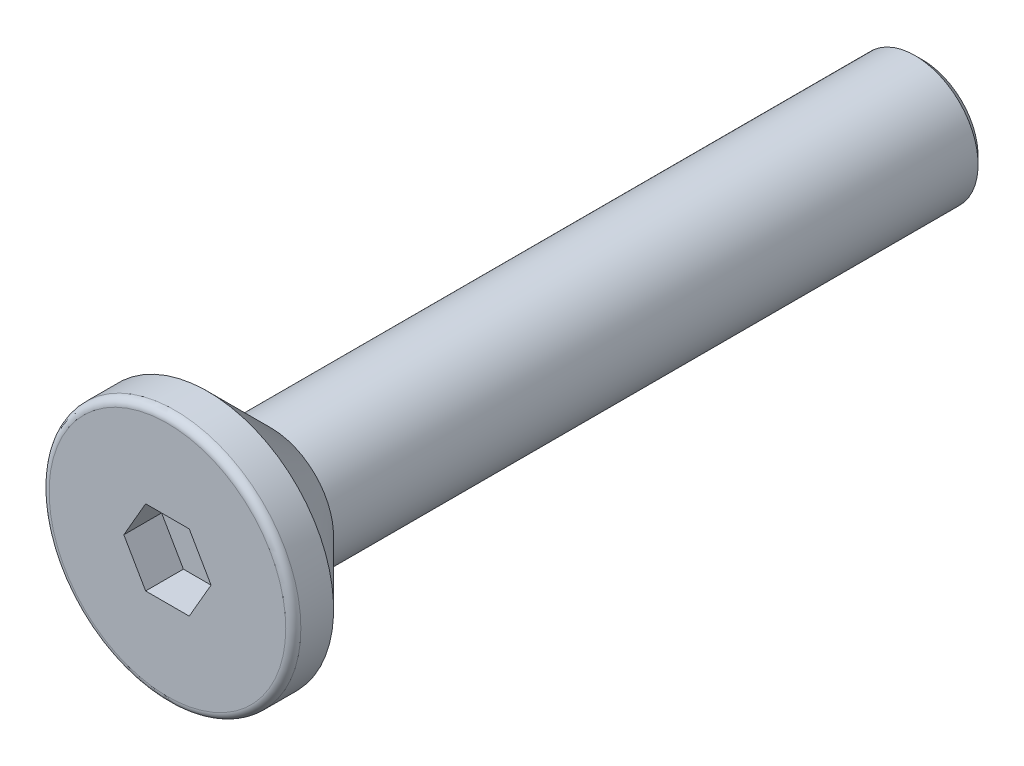
SolidWorks part; units mm, degrees
ref_plane "前视基准面" through (0, 0, 0) normal (0, 0, 1) x (1, 0, 0)
ref_plane "上视基准面" through (0, 0, 0) normal (0, 1, 0) x (1, 0, 0)
ref_plane "右视基准面" through (0, 0, 0) normal (1, 0, 0) x (0, 0, -1)
sketch "草图1" plane through (0, 0, 0) normal (1, 0, 0) x (0, 0, -1)
  line L0 (-15, 0) -> (-15, 5)
  line L1 (-15, 5) -> (-13.4, 5)
  line L2 (-13.4, 5) -> (-10.9, 2.5)
  line L3 (-10.9, 2.5) -> (14.7, 2.5)
  line L4 (14.7, 2.5) -> (15, 2.2)
  line L5 (15, 2.2) -> (15, 0)
  line L6 (15, 0) -> (-15, 0)
  dimension "D1" = 30
  dimension "D2" = 5
  dimension "D3" = 45
  dimension "D4" = 0.3
  dimension "D5" = 4.1
  dimension "D6" = 2.5
revolve "旋转1" add sketch "草图1" angle 360 about L6
sketch "草图2" plane through (0, 0, 15) normal (0, 0, 1) x (1, 0, 0)
  line L1 (1.7321, 0) -> (0.866, 1.5)
  line L2 (0.866, 1.5) -> (-0.866, 1.5)
  line L3 (-0.866, 1.5) -> (-1.7321, 0)
  line L4 (-1.7321, 0) -> (-0.866, -1.5)
  line L5 (-0.866, -1.5) -> (0.866, -1.5)
  line L6 (0.866, -1.5) -> (1.7321, 0)
  circle A0 centre (0, 0) radius 1.5 construction
  dimension "D1" = 3
extrude "切除-拉伸1" cut sketch "草图2" against normal blind 1.5
fillet "圆角1" radius 0.3 1 edges at (-5, 0, 15)
